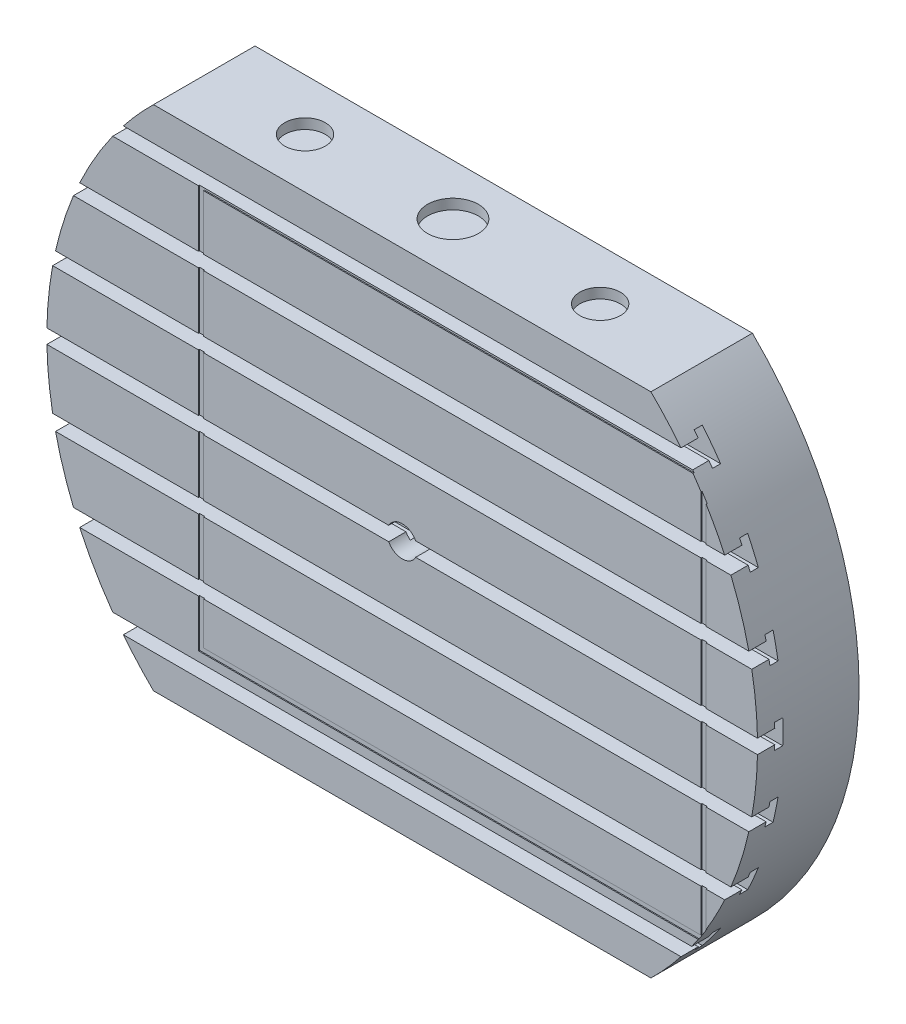
SolidWorks part; units mm, degrees
material "Plain Carbon Steel"
ref_plane "Front Plane" through (0, 0, 0) normal (0, 0, 1) x (1, 0, 0)
ref_plane "Top Plane" through (0, 0, 0) normal (0, 1, 0) x (1, 0, 0)
ref_plane "Right Plane" through (0, 0, 0) normal (1, 0, 0) x (0, 0, -1)
sketch "Sketch1" plane through (0, 0, 0) normal (0, 0, 1) x (1, 0, 0)
  circle A0 centre (0, 0) radius 350
  circle A1 centre (0, 0) radius 15
  dimension "D1" = 700
  dimension "D2" = 30
extrude "Boss-Extrude1" add sketch "Sketch1" along normal blind 100
sketch "Sketch2" plane through (0, 0, 0) normal (1, 0, 0) x (0, 0, -1)
  line L0 (-100, 7) -> (-83, 7)
  line L1 (-100, 350) -> (-100, -350) construction
  line L2 (-83, 7) -> (-83, 12)
  line L3 (-83, 12) -> (-75, 12)
  line L4 (-75, 12) -> (-75, -12)
  line L5 (-75, -12) -> (-83, -12)
  line L6 (-83, -12) -> (-83, -7)
  line L7 (-83, -7) -> (-100, -7)
  line L8 (-100, -7) -> (-100, 7)
  line L9 (-100, 0) -> (-75, 0) construction
  line L10 (-83, 7) -> (-83, -7) construction
  line L11 (-100, -77) -> (-100, -63)
  line L12 (-100, -63) -> (-83, -63)
  line L13 (-83, -77) -> (-100, -77)
  line L14 (-83, -82) -> (-83, -77)
  line L15 (-75, -82) -> (-83, -82)
  line L16 (-75, -58) -> (-75, -82)
  line L17 (-83, -58) -> (-75, -58)
  line L18 (-83, -63) -> (-83, -58)
  line L19 (-100, -147) -> (-100, -133)
  line L20 (-100, -133) -> (-83, -133)
  line L21 (-83, -147) -> (-100, -147)
  line L22 (-83, -152) -> (-83, -147)
  line L23 (-75, -152) -> (-83, -152)
  line L24 (-75, -128) -> (-75, -152)
  line L25 (-83, -128) -> (-75, -128)
  line L26 (-83, -133) -> (-83, -128)
  line L27 (-100, -217) -> (-100, -203)
  line L28 (-100, -203) -> (-83, -203)
  line L29 (-83, -217) -> (-100, -217)
  line L30 (-83, -222) -> (-83, -217)
  line L31 (-75, -222) -> (-83, -222)
  line L32 (-75, -198) -> (-75, -222)
  line L33 (-83, -198) -> (-75, -198)
  line L34 (-83, -203) -> (-83, -198)
  line L43 (0, -350) -> (0, 350) construction
  line L44 (-100, -350) -> (0, -350)
  line L45 (-100, -350) -> (-100, -250)
  line L46 (-100, -250) -> (0, -250)
  line L47 (0, -350) -> (0, -250)
  line L48 (-100, 63) -> (-100, 77)
  line L49 (-100, 350) -> (0, 350)
  line L50 (-100, 350) -> (-100, 250)
  line L51 (-100, 250) -> (0, 250)
  line L52 (0, 350) -> (0, 250)
  line L53 (-83, 63) -> (-100, 63)
  line L54 (-83, 58) -> (-83, 63)
  line L55 (-75, 58) -> (-83, 58)
  line L56 (-75, 82) -> (-75, 58)
  line L57 (-83, 82) -> (-75, 82)
  line L58 (-83, 77) -> (-83, 82)
  line L59 (-100, 77) -> (-83, 77)
  line L60 (-100, 133) -> (-100, 147)
  line L61 (-83, 133) -> (-100, 133)
  line L62 (-83, 128) -> (-83, 133)
  line L63 (-75, 128) -> (-83, 128)
  line L64 (-75, 152) -> (-75, 128)
  line L65 (-83, 152) -> (-75, 152)
  line L66 (-83, 147) -> (-83, 152)
  line L67 (-100, 147) -> (-83, 147)
  line L68 (-100, 203) -> (-100, 217)
  line L69 (-83, 203) -> (-100, 203)
  line L70 (-83, 198) -> (-83, 203)
  line L71 (-75, 198) -> (-83, 198)
  line L72 (-75, 222) -> (-75, 198)
  line L73 (-83, 222) -> (-75, 222)
  line L74 (-83, 217) -> (-83, 222)
  line L75 (-100, 217) -> (-83, 217)
  dimension "D1" = 14
  dimension "D2" = 24
  dimension "D3" = 17
  dimension "D4" = 8
  dimension "D6" = 56
  dimension "D7" = 100
  dimension "D8" = 100
  dimension "D10" = 56
  dimension "D5" = 4
  dimension "D9" = 4
extrude "Cut-Extrude1" cut sketch "Sketch2" against normal mid plane 1000
sketch "Sketch3" plane through (0, 0, 100) normal (0, 0, 1) x (1, 0, 0)
  line L0 (-195.66, 201.2164) -> (294.34, 201.2164)
  line L1 (-200.66, -193.7836) -> (299.34, -193.7836)
  line L2 (-200.66, -193.7836) -> (-200.66, 206.2164)
  line L3 (-200.66, 206.2164) -> (299.34, 206.2164)
  line L4 (299.34, -193.7836) -> (299.34, 206.2164)
  line L5 (0, 206.2164) -> (0, -193.7836) construction
  line L6 (-200.66, 0) -> (299.34, 0) construction
  line L7 (294.34, -188.7836) -> (294.34, 201.2164)
  line L8 (-195.66, -188.7836) -> (294.34, -188.7836)
  line L9 (-195.66, -188.7836) -> (-195.66, 201.2164)
  dimension "D1" = 500
  dimension "D2" = 400
  dimension "D3" = 200.66
  dimension "D4" = 193.7836
  dimension "D5" = 5
extrude "Cut-Extrude2" cut sketch "Sketch3" against normal blind 1
sketch "Sketch4" plane through (0, 250, 0) normal (0, -1, 0) x (1, 0, 0)
  line L0 (-244.949, 50) -> (244.949, 50) construction
  line L1 (-244.949, 0) -> (-244.949, 100) construction
  line L2 (244.949, 100) -> (244.949, 0) construction
  circle A0 centre (0, 50) radius 25
  circle A1 centre (144.949, 50) radius 20
  circle A2 centre (-144.949, 50.7642) radius 20
  point P12 (0, 0)
  point P13 (154.4258, 55.6666)
  point P14 (138.3815, 50)
  point P15 (0, 0)
  dimension "D1" = 50
  dimension "D2" = 40
  dimension "D3" = 40
  dimension "D4" = 100
  dimension "D5" = 100
extrude "Cut-Extrude3" cut sketch "Sketch4" along normal blind 10
